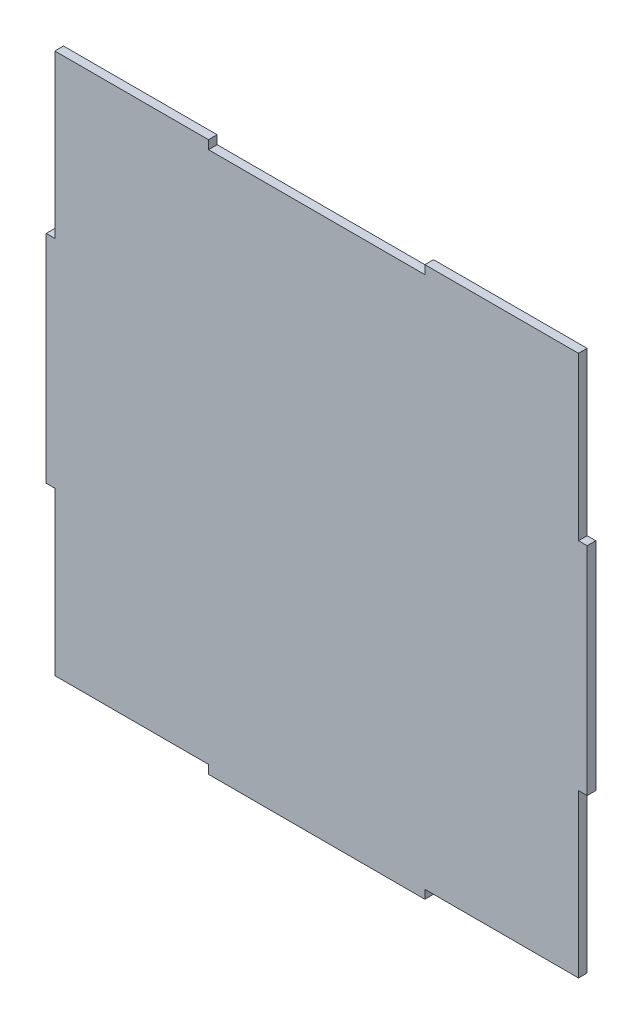
SolidWorks part; units mm, degrees
ref_plane "Front Plane" through (0, 0, 0) normal (0, 0, 1) x (1, 0, 0)
ref_plane "Top Plane" through (0, 0, 0) normal (0, 1, 0) x (1, 0, 0)
ref_plane "Right Plane" through (0, 0, 0) normal (1, 0, 0) x (0, 0, -1)
sketch "Sketch1" plane through (0, 0, 0) normal (0, 0, 1) x (1, 0, 0)
  line L0 (-49.637, 1.5462) -> (-49.637, -2.4538)
  line L1 (-49.637, -2.4538) -> (50.363, -2.4538)
  line L2 (50.363, -2.4538) -> (50.363, 1.5462)
  line L3 (-49.637, 1.5462) -> (-120.637, 1.5462)
  line L4 (-120.637, 1.5462) -> (-120.637, 76.5462)
  line L5 (-120.637, 76.5462) -> (-124.637, 76.5462)
  line L6 (-124.637, 76.5462) -> (-124.637, 176.5462)
  line L7 (-124.637, 176.5462) -> (-120.637, 176.5462)
  line L8 (-120.637, 176.5462) -> (-120.637, 251.5462)
  line L9 (-120.637, 251.5462) -> (-49.637, 251.5462)
  line L10 (-49.637, 251.5462) -> (-49.637, 247.5462)
  line L11 (-49.637, 247.5462) -> (50.363, 247.5462)
  line L12 (50.363, 247.5462) -> (50.363, 251.5462)
  line L13 (50.363, 251.5462) -> (121.363, 251.5462)
  line L14 (121.363, 251.5462) -> (121.363, 176.5462)
  line L15 (121.363, 176.5462) -> (125.363, 176.5462)
  line L16 (125.363, 176.5462) -> (125.363, 76.5462)
  line L17 (125.363, 76.5462) -> (121.363, 76.5462)
  line L18 (121.363, 76.5462) -> (121.363, 1.5462)
  line L19 (121.363, 1.5462) -> (50.363, 1.5462)
extrude "Boss-Extrude1" add sketch "Sketch1" along normal blind 4
